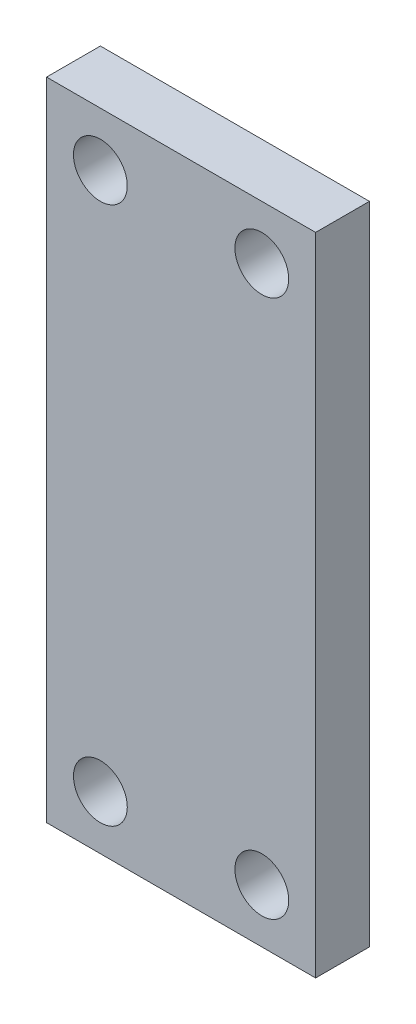
SolidWorks part; units mm, degrees
ref_plane "前视基准面" through (0, 0, 0) normal (0, 0, 1) x (1, 0, 0)
ref_plane "上视基准面" through (0, 0, 0) normal (0, 1, 0) x (1, 0, 0)
ref_plane "右视基准面" through (0, 0, 0) normal (1, 0, 0) x (0, 0, -1)
other "Configuration Table"
sketch "Sketch1" plane through (0, 0, 0) normal (0, 0, 1) x (1, 0, 0)
  line L0 (0, 0) -> (0, 25) construction
  line L1 (-12.5, -30) -> (12.5, -30)
  line L2 (-12.5, -30) -> (-12.5, 30)
  line L3 (-12.5, 30) -> (12.5, 30)
  line L4 (12.5, -30) -> (12.5, 30)
  line L5 (-12.5, -30) -> (12.5, 30) construction
  line L6 (-12.5, 30) -> (12.5, -30) construction
  line L7 (0, 25) -> (7.5, 25) construction
  line L8 (0, 0) -> (12.5, 0) construction
  circle A0 centre (7.5, 25) radius 2.5
  circle A1 centre (-7.5, 25) radius 2.5
  circle A2 centre (7.5, -25) radius 2.5
  circle A3 centre (-7.5, -25) radius 2.5
  point P0 (0, 0)
  dimension "D3" = 5
  dimension "D1" = 60
  dimension "D2" = 25
  dimension "D4" = 7.5
  dimension "D5" = 25
extrude "Boss-Extrude1" add sketch "Sketch1" along normal blind 5
